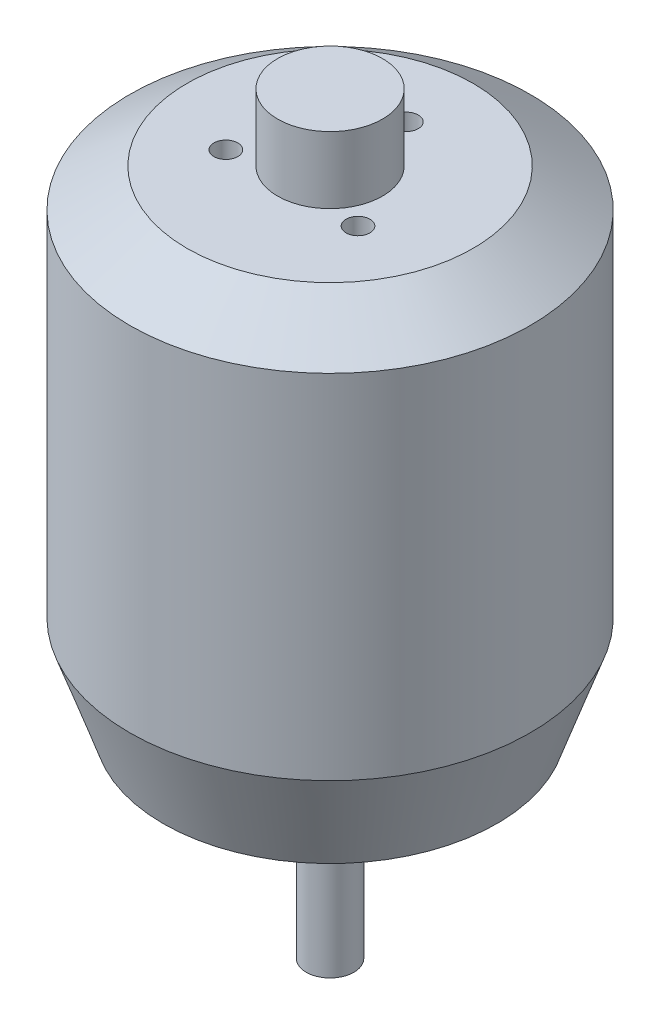
SolidWorks part; units mm, degrees
ref_plane "Front" through (0, 0, 0) normal (0, 0, 1) x (1, 0, 0)
ref_plane "Top" through (0, 0, 0) normal (0, 1, 0) x (1, 0, 0)
ref_plane "Right" through (0, 0, 0) normal (1, 0, 0) x (0, 0, -1)
sketch "Sketch1" plane through (0, 0, 0) normal (0, 1, 0) x (1, 0, 0)
  circle A0 centre (0, 0) radius 17.5
  dimension "D1" = 35
extrude "Boss-Extrude1" add sketch "Sketch1" along normal blind 10 contours A0
sketch "Sketch2" plane through (0, 10, 0) normal (0, 1, 0) x (1, 0, 0)
  circle A0 centre (0, 0) radius 21
  dimension "D1" = 42
extrude "Boss-Extrude2" add sketch "Sketch2" along normal blind 37
sketch "Sketch3" plane through (0, 47, 0) normal (0, 1, 0) x (1, 0, 0)
  circle A0 centre (0, 0) radius 15
  dimension "D1" = 30
extrude "Boss-Extrude3" add sketch "Sketch3" along normal blind 4
sketch "Sketch4" plane through (0, 51, 0) normal (0, 1, 0) x (1, 0, 0)
  circle A0 centre (0, 0) radius 5.5
  dimension "D1" = 11
extrude "Boss-Extrude4" add sketch "Sketch4" along normal blind 7
sketch "Sketch5" plane through (0, 0, 0) normal (0, -1, 0) x (1, 0, 0)
  circle A0 centre (0, 0) radius 2.5
  dimension "D1" = 5
extrude "Boss-Extrude5" add sketch "Sketch5" along normal blind 21
loft "Loft1" add section edge at (0, 0, 17.5) section edge at (0, 10, 21)
loft "Loft2" add section edge at (0, 51, 15) section edge at (0, 47, 21)
sketch "Sketch6" plane through (0, 0, 0) normal (0, -1, 0) x (1, 0, 0)
  line L0 (0, 0) -> (-16.3695, 16.3695) construction
  circle A0 centre (0, 12.5) radius 1.5
  circle A1 centre (12.5, 0) radius 1.5
  circle A2 centre (0, -12.5) radius 1.5
  circle A3 centre (-12.5, 0) radius 1.5
  circle A4 centre (-8.8388, 8.8388) radius 4
  circle A5 centre (8.8388, 8.8388) radius 4
  circle A6 centre (8.8388, -8.8388) radius 4
  circle A7 centre (-8.8388, -8.8388) radius 4
  point P12 (0, 0)
  point P24 (0, 0)
  dimension "D1" = 3
  dimension "D5" = 8
  dimension "D2" = 12.5
  dimension "D4" = 12.5
  dimension "D3" = 4
  dimension "D6" = 4
extrude "Cut-Extrude1" cut sketch "Sketch6" against normal blind 10
sketch "Sketch7" plane through (0, 0, 0) normal (0, -1, 0) x (1, 0, 0)
  circle A0 centre (0, 0) radius 5.25
  dimension "D1" = 10.5
extrude "Boss-Extrude6" add sketch "Sketch7" along normal blind 6.5
sketch "Sketch9" plane through (0, 51, 0) normal (0, 1, 0) x (1, 0, 0)
  circle A0 centre (0, 8) radius 1.25
  circle A1 centre (6.9282, -4) radius 1.25
  circle A2 centre (-6.9282, -4) radius 1.25
  point P9 (0, 0)
  dimension "D1" = 2.5
  dimension "D2" = 8
  dimension "D3" = 3
extrude "Cut-Extrude2" cut sketch "Sketch9" against normal blind 10
sketch "Sketch10" plane through (0, 0, 0) normal (0, -1, 0) x (1, 0, 0)
  line L0 (-24, 6) -> (-12, 6)
  line L5 (-30, 30) -> (30, -30) construction
  line L6 (-30, -30) -> (30, 30) construction
  line L7 (-6, 12) -> (-6, 24)
  line L8 (6, 24) -> (6, 12)
  line L9 (12, 6) -> (24, 6)
  line L10 (24, -6) -> (12, -6)
  line L11 (6, -12) -> (6, -24)
  line L12 (-6, -24) -> (-6, -12)
  line L13 (-12, -6) -> (-24, -6)
  circle A0 centre (0, 12.5) radius 1.5
  arc A1 (-30, 0) -> (-24, 6) centre (-24, 0) cw
  arc A2 (-12, 6) -> (-6, 12) centre (-12, 12) ccw
  arc A3 (0, 30) -> (-6, 24) centre (0, 24) ccw
  arc A4 (0, 30) -> (6, 24) centre (0, 24) cw
  arc A5 (6, 12) -> (12, 6) centre (12, 12) ccw
  arc A6 (30, 0) -> (24, 6) centre (24, 0) ccw
  arc A7 (30, 0) -> (24, -6) centre (24, 0) cw
  arc A8 (12, -6) -> (6, -12) centre (12, -12) ccw
  arc A9 (0, -30) -> (6, -24) centre (0, -24) ccw
  arc A10 (0, -30) -> (-6, -24) centre (0, -24) cw
  arc A11 (-6, -12) -> (-12, -6) centre (-12, -12) ccw
  arc A12 (-30, 0) -> (-24, -6) centre (-24, 0) ccw
  circle A13 centre (-12.5, 0) radius 1.5
  circle A14 centre (-25, 0) radius 1.5
  circle A15 centre (0, 25) radius 1.5
  circle A16 centre (12.5, 0) radius 1.5
  circle A17 centre (25, 0) radius 1.5
  circle A18 centre (0, -12.5) radius 1.5
  circle A19 centre (0, -25) radius 1.5
  point P0 (0, 0)
  point P13 (-6, 6)
  point P46 (0, 0)
  point P60 (0, 0)
  dimension "D1" = 6
  dimension "D2" = 6
  dimension "D3" = 6
  dimension "D5" = 25
  dimension "D6" = 3
  dimension "D4" = 4
  dimension "D7" = 4
extrude "Boss-Extrude7" [suppressed] add sketch "Sketch10" along normal blind 3
chamfer "Chamfer1" [suppressed] distance 1.5 angle 60
